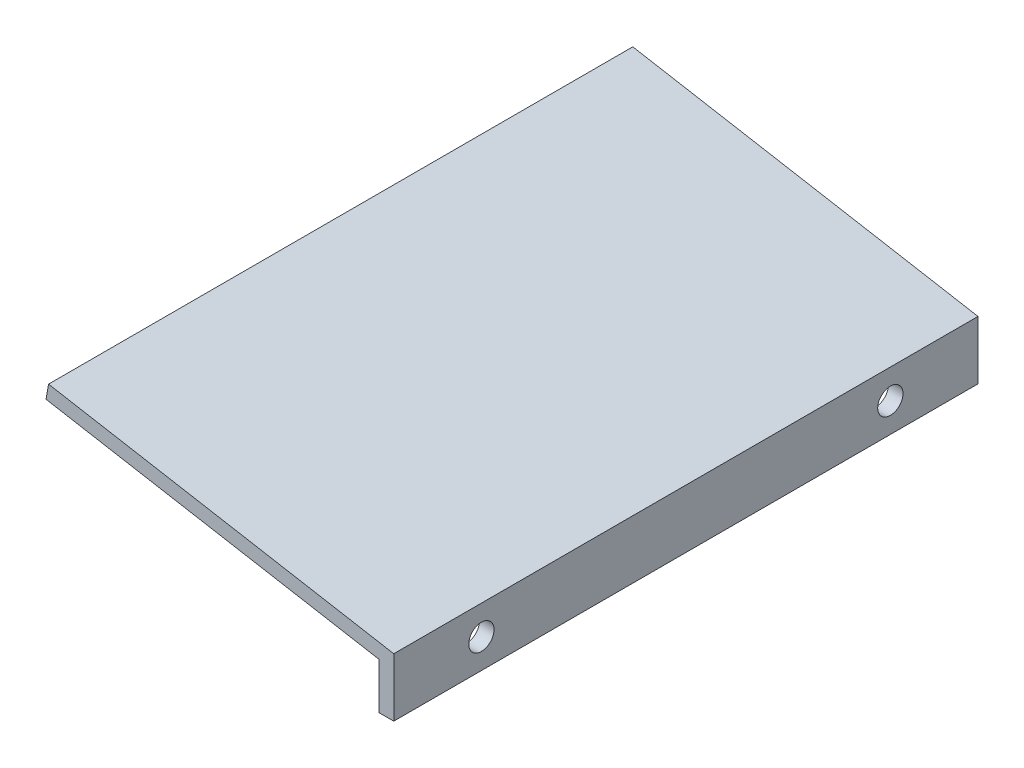
SolidWorks part; units mm, degrees
ref_plane "Front Plane" through (0, 0, 0) normal (0, 0, 1) x (1, 0, 0)
ref_plane "Top Plane" through (0, 0, 0) normal (0, 1, 0) x (1, 0, 0)
ref_plane "Right Plane" through (0, 0, 0) normal (1, 0, 0) x (0, 0, -1)
sketch "Sketch1" plane through (0, 0, 0) normal (0, 0, 1) x (1, 0, 0)
  line L0 (0, 0) -> (0, 10.0359)
  line L1 (0, 10.0359) -> (-72.4187, 22.8052)
  line L2 (-72.4187, 22.8052) -> (-71.8674, 25.932)
  line L3 (-71.8674, 25.932) -> (3.175, 12.7)
  line L4 (3.175, 12.7) -> (3.175, 0)
  line L5 (3.175, 0) -> (0, 0)
  dimension "D1" = 100
  dimension "D2" = 3.175
  dimension "D3" = 3.175
  dimension "D4" = 12.7
  dimension "D5" = 76.2
extrude "Boss-Extrude1" add sketch "Sketch1" along normal blind 127
sketch "Sketch2" plane through (3.175, 0, 0) normal (1, 0, 0) x (0, 0, -1)
  line L0 (-127, 0) -> (0, 0) construction
  line L2 (-127, 0) -> (-127, 12.7) construction
  line L3 (0, 0) -> (0, 12.7) construction
  point P1 (-107.95, 6.35)
  point P3 (-19.05, 6.35)
  point P6 (0, 0)
  point P12 (0, 0)
  dimension "D1" = 6.35
  dimension "D4" = 19.05
  dimension "D5" = 19.05
hole_wizard "M5 Clearance Hole1" positions "Sketch3" profile "Sketch4" hole size "M5" standard "ANSI Metric" end condition through all
sketch "Sketch3" plane through (3.175, 0, 0) normal (1, 0, 0) x (0, 0, -1)
  point P0 (-107.95, 6.35)
  point P3 (-19.05, 6.35)
sketch "Sketch4" plane through (3.175, 6.35, 107.95) normal (0, 1, 0) x (0, 0, -1)
  line L0 (0, 0) -> (0, 75.5937)
  line L1 (0, 75.5937) -> (2.75, 75.5937)
  line L2 (2.75, 75.5937) -> (2.75, 0)
  line L5 (2.75, 0) -> (0, 0)
  line L11 (0, -6.35) -> (0, 107.95) construction
  dimension "Thru Hole Dia." = 5.5
  dimension "Thru Hole Depth" = 75.5937
